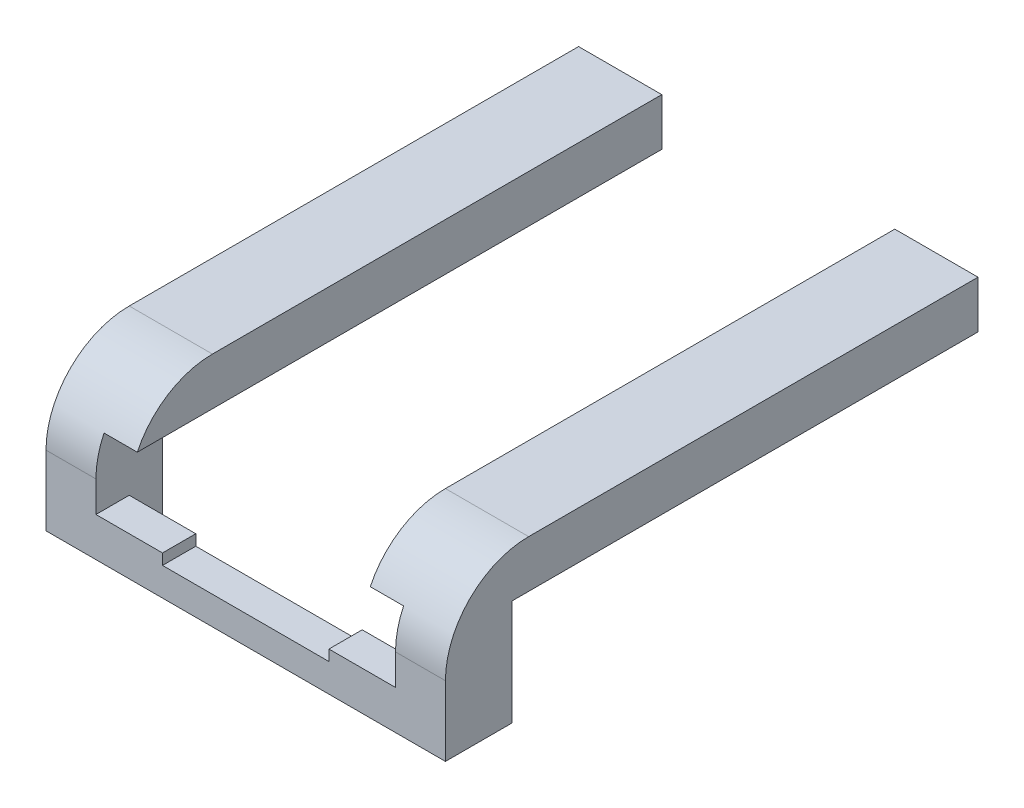
SolidWorks part; units mm, degrees
ref_plane "Plan de face" through (0, 0, 0) normal (0, 0, 1) x (1, 0, 0)
ref_plane "Plan de dessus" through (0, 0, 0) normal (0, 1, 0) x (1, 0, 0)
ref_plane "Plan de droite" through (0, 0, 0) normal (1, 0, 0) x (0, 0, -1)
sketch "Esquisse1" plane through (0, 0, 0) normal (0, 1, 0) x (1, 0, 0)
  line L0 (0, 10.7653) -> (0, 0) construction
  line L1 (-12, 4) -> (-9, 4)
  line L2 (-12, 4) -> (-12, 0)
  line L3 (-12, 0) -> (12, 0)
  line L4 (9, 4) -> (9, 2)
  line L5 (12, 4) -> (9, 4)
  line L6 (12, 4) -> (12, 0)
  line L7 (-9, 4) -> (-9, 2)
  line L8 (-9, 2) -> (9, 2)
  point P11 (0, 0)
  point P14 (0, 2)
  dimension "D1" = 12
  dimension "D2" = 3
  dimension "D3" = 2
  dimension "D4" = 4
extrude "Boss.-Extru.1" add sketch "Esquisse1" along normal blind 1.7
sketch "Esquisse2" plane through (0, 1.7, 0) normal (0, 1, 0) x (1, 0, 0)
  line L0 (0, 10.37) -> (0, -2.9456) construction
  line L1 (-12, 4) -> (-9, 4)
  line L2 (-12, 4) -> (-12, 0)
  line L3 (-12, 0) -> (-9, 0)
  line L4 (-9, 4) -> (-9, 0)
  line L5 (9, 4) -> (9, 0)
  line L6 (12, 0) -> (9, 0)
  line L7 (12, 4) -> (12, 0)
  line L8 (12, 4) -> (9, 4)
extrude "Boss.-Extru.2" add sketch "Esquisse2" along normal blind 7.5
sketch "Esquisse3" plane through (0, 9.2, 0) normal (0, 1, 0) x (1, 0, 0)
  line L0 (0, 19.4908) -> (0, -10.6066) construction
  line L1 (-12, 0) -> (-7, 0)
  line L2 (-12, 0) -> (-12, 32)
  line L3 (-12, 32) -> (-7, 32)
  line L4 (-7, 0) -> (-7, 32)
  line L5 (7, 0) -> (7, 32)
  line L6 (12, 32) -> (7, 32)
  line L7 (12, 0) -> (12, 32)
  line L8 (12, 0) -> (7, 0)
  dimension "D1" = 5
  dimension "D2" = 32
extrude "Boss.-Extru.3" add sketch "Esquisse3" against normal blind 2.85
fillet "Congé1" radius 5 2 edges at (9.5, 9.2, 0) (-9.5, 9.2, 0)
sketch "Esquisse4" plane through (0, 1.7, 0) normal (0, 1, 0) x (1, 0, 0)
  line L0 (9, 2) -> (-9, 2) construction
  line L1 (-9, 0) -> (-5, 0)
  line L2 (-9, 0) -> (-9, 2)
  line L3 (-9, 2) -> (-5, 2)
  line L4 (-5, 0) -> (-5, 2)
  line L6 (0, 5.1742) -> (0, -2.8534) construction
  line L7 (5, 0) -> (5, 2)
  line L8 (9, 2) -> (5, 2)
  line L9 (9, 0) -> (9, 2)
  line L10 (9, 0) -> (5, 0)
  point P16 (-5, 1)
  dimension "D1" = 5
extrude "Boss.-Extru.4" add sketch "Esquisse4" along normal blind 0.65
